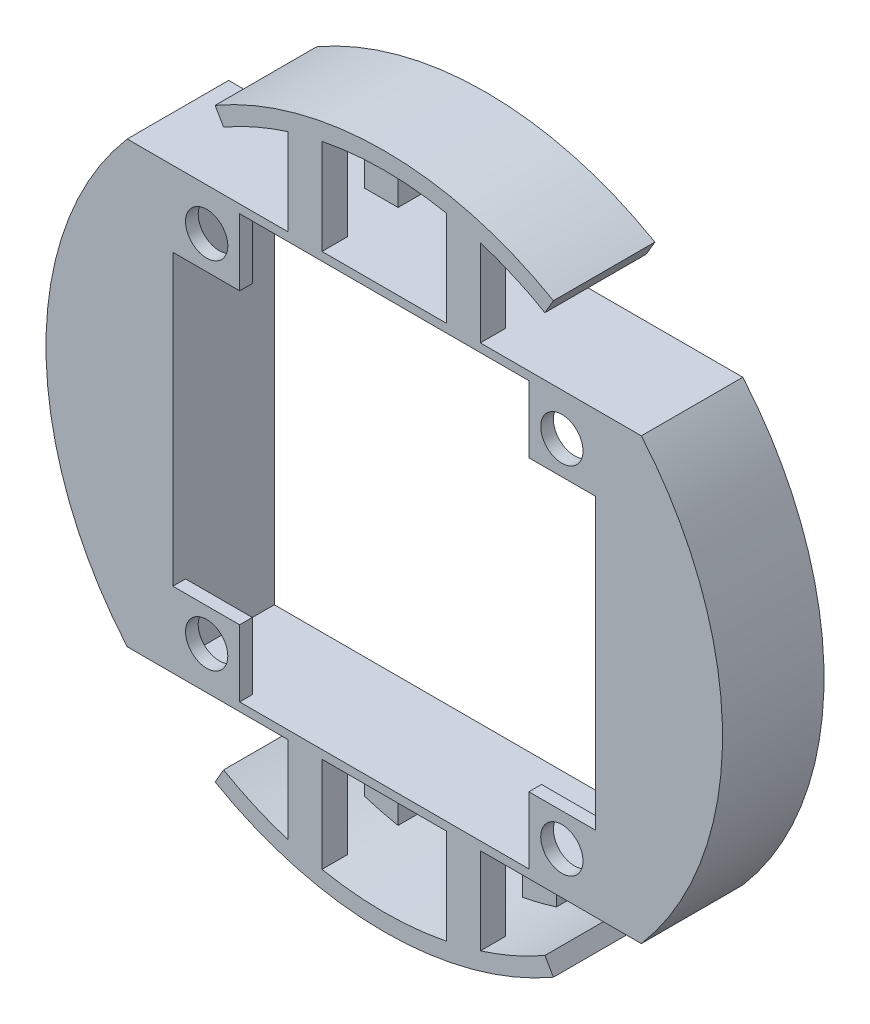
SolidWorks part; units mm, degrees
ref_plane "Front Plane" through (0, 0, 0) normal (0, 0, 1) x (1, 0, 0)
ref_plane "Top Plane" through (0, 0, 0) normal (0, 1, 0) x (1, 0, 0)
ref_plane "Right Plane" through (0, 0, 0) normal (1, 0, 0) x (0, 0, -1)
sketch "Sketch1" plane through (0, 0, 0) normal (0, 0, 1) x (1, 0, 0)
  line L0 (0, 0) -> (0, 25) construction
  line L1 (-25, -25) -> (25, -25)
  line L2 (-25, -25) -> (-25, 25)
  line L3 (-25, 25) -> (25, 25)
  line L4 (25, -25) -> (25, 25)
  line L5 (-25, -25) -> (25, 25) construction
  line L6 (-25, 25) -> (25, -25) construction
  line L9 (-19, 32.909) -> (-20, 34.641)
  line L11 (0, 0) -> (0, -40) construction
  line L12 (19, -32.909) -> (20, -34.641)
  line L14 (-30.3974, 26) -> (-26, 26)
  line L15 (-19, -32.909) -> (-20, -34.641)
  line L16 (-30.3974, -26) -> (-26, -26)
  line L18 (-26, -26) -> (23.9583, -26)
  line L20 (-26, 26) -> (23.9583, 26)
  line L22 (-25, -25) -> (26, 26) construction
  line L23 (-25, 25) -> (26, -26) construction
  line L24 (23.9583, -26) -> (30.3974, -26)
  line L25 (23.9583, 26) -> (30.3974, 26)
  line L26 (20, 34.641) -> (19, 32.909)
  arc A1 (-19, -32.909) -> (19, -32.909) centre (0, 0) ccw
  arc A2 (-19, 32.909) -> (19, 32.909) centre (0, 0) cw
  arc A5 (20, 34.641) -> (-20, 34.641) centre (0, 0) ccw
  arc A7 (-30.3974, 26) -> (-30.3974, -26) centre (0, 0) ccw
  arc A8 (-20, -34.641) -> (20, -34.641) centre (0, 0) ccw
  arc A9 (30.3974, -26) -> (30.3974, 26) centre (0, 0) ccw
  dimension "D2" = 76
  dimension "D3" = 50
  dimension "D4" = 50
  dimension "D5" = 52
  dimension "D6" = 30
  dimension "D7" = 30
  dimension "D8" = 52
extrude "Boss-Extrude1" add sketch "Sketch1" along normal blind 12
sketch "Sketch2" plane through (0, 0, 12) normal (0, 0, 1) x (1, 0, 0)
  line L1 (25, 25) -> (-25, 25) construction
  line L2 (-11.3655, 37.2794) -> (-7.3655, 37.2794)
  line L3 (-11.3655, 37.2794) -> (-11.3655, 25)
  line L4 (-11.3655, 25) -> (-7.3655, 25)
  line L5 (-7.3655, 37.2794) -> (-7.3655, 25)
  line L7 (7.3655, 37.2794) -> (11.3655, 37.2794)
  line L8 (7.3655, 37.2794) -> (7.3655, 25)
  line L9 (7.3655, 25) -> (11.3655, 25)
  line L10 (11.3655, 37.2794) -> (11.3655, 25)
  line L11 (7.3655, -25) -> (11.3655, -25)
  line L12 (11.3655, -37.2794) -> (11.3655, -25)
  line L13 (7.3655, -37.2794) -> (11.3655, -37.2794)
  line L14 (7.3655, -37.2794) -> (7.3655, -25)
  line L15 (-11.3655, -25) -> (-7.3655, -25)
  line L16 (-7.3655, -37.2794) -> (-7.3655, -25)
  line L17 (-11.3655, -37.2794) -> (-7.3655, -37.2794)
  line L18 (-11.3655, -37.2794) -> (-11.3655, -25)
  arc A0 (19, 32.909) -> (-19, 32.909) centre (0, 0) ccw construction
  arc A1 (-19, -32.909) -> (19, -32.909) centre (0, 0) ccw construction
  point P1 (0, 0)
  point P2 (0, 0)
  point P3 (0, 0)
  point P7 (0, 0)
  point P12 (0, 0)
  point P21 (0, 0)
  dimension "D1" = 4
  dimension "D2" = 4
  dimension "D3" = 4
extrude "Boss-Extrude2" add sketch "Sketch2" against normal blind 3
sketch "Sketch3" plane through (0, 0, 0) normal (0, 0, -1) x (-1, 0, 0)
  line L0 (-25, 25) -> (25, 25) construction
  line L5 (25, -25) -> (-25, -25) construction
  line L14 (-7.3655, 37.2794) -> (-7.3655, 26) construction
  line L23 (-11.3655, 25) -> (-7.3655, 25)
  line L24 (-11.3655, 25) -> (-11.3655, 37.2442)
  line L25 (-11.3655, 37.2442) -> (-7.3655, 37.2442)
  line L26 (-7.3655, 25) -> (-7.3655, 37.2442)
  line L28 (11.3655, 25) -> (7.3655, 25)
  line L29 (11.3655, 25) -> (11.3655, 37.2794)
  line L30 (11.3655, 37.2794) -> (7.3655, 37.2794)
  line L31 (7.3655, 25) -> (7.3655, 37.2794)
  line L32 (-11.3655, -25) -> (-7.3655, -25)
  line L33 (-11.3655, -25) -> (-11.3655, -37.2794)
  line L34 (-11.3655, -37.2794) -> (-7.3655, -37.2794)
  line L35 (-7.3655, -25) -> (-7.3655, -37.2794)
  line L36 (11.3655, -25) -> (7.3655, -25)
  line L37 (11.3655, -25) -> (11.3655, -37.2794)
  line L38 (11.3655, -37.2794) -> (7.3655, -37.2794)
  line L39 (7.3655, -25) -> (7.3655, -37.2794)
  arc A4 (-19, -32.909) -> (19, -32.909) centre (0, 0) ccw construction
  arc A5 (7.3655, -37.2794) -> (11.3655, -36.2605) centre (0, 0) ccw construction
  dimension "D1" = 4
  dimension "D2" = 4
  dimension "D3" = 4
  dimension "D4" = 4
extrude "Boss-Extrude3" add sketch "Sketch3" against normal blind 3
sketch "Sketch4" plane through (0, 0, 12) normal (0, 0, 1) x (1, 0, 0)
  line L1 (-30.3974, -26) -> (-17.0995, -26)
  line L2 (-30.3974, -26) -> (-30.3974, -17.1)
  line L3 (-30.3974, -17.1) -> (-17.0995, -17.1)
  line L4 (-17.0995, -26) -> (-17.0995, -17.1)
  line L10 (30.3974, -17.1) -> (17.0995, -17.1)
  line L11 (17.0995, -26) -> (17.0995, -17.1)
  line L12 (30.3974, -26) -> (17.0995, -26)
  line L13 (30.3974, -26) -> (30.3974, -17.1)
  line L14 (30.3974, 26) -> (30.3974, 17.1)
  line L15 (30.3974, 26) -> (17.0995, 26)
  line L16 (17.0995, 26) -> (17.0995, 17.1)
  line L17 (30.3974, 17.1) -> (17.0995, 17.1)
  line L18 (-30.3974, 17.1) -> (-17.0995, 17.1)
  line L19 (-17.0995, 26) -> (-17.0995, 17.1)
  line L20 (-30.3974, 26) -> (-17.0995, 26)
  line L21 (-30.3974, 26) -> (-30.3974, 17.1)
  circle A0 centre (-21, -21) radius 2.5
  circle A1 centre (21, -21) radius 2.5
  circle A2 centre (21, 21) radius 2.5
  circle A3 centre (-21, 21) radius 2.5
  point P12 (0, 0)
  point P16 (0, 0)
  dimension "D3" = 5
  dimension "D4" = 3.9005
  dimension "D5" = 3.9
extrude "Boss-Extrude4" add sketch "Sketch4" against normal blind 1.5
